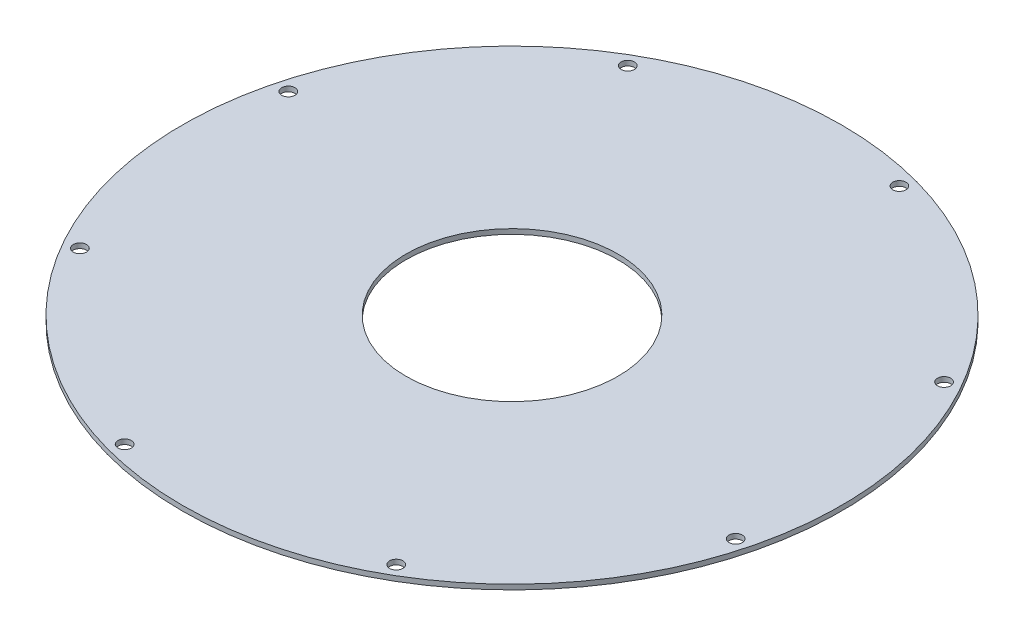
SolidWorks part; units mm, degrees
material "Thornel Mat VMA"
ref_plane "Front Plane" through (0, 0, 0) normal (0, 0, 1) x (1, 0, 0)
ref_plane "Top Plane" through (0, 0, 0) normal (0, 1, 0) x (1, 0, 0)
ref_plane "Right Plane" through (0, 0, 0) normal (1, 0, 0) x (0, 0, -1)
sketch "Sketch1" plane through (0, 0, 0) normal (0, 1, 0) x (1, 0, 0)
  circle A0 centre (0, 0) radius 32
  circle A1 centre (0, 0) radius 99.5
  dimension "D1" = 64
  dimension "D2" = 199
extrude "Base" add sketch "Sketch1" along normal mid plane 1.5
sketch "Sketch2" plane through (0, 0.75, 0) normal (0, 1, 0) x (1, 0, 0)
  line L0 (24.7172, 92.2459) -> (25.7525, 96.1096) construction
  line L1 (24.7172, 92.2459) -> (0, 0) construction
  line L2 (0, 0) -> (0, 99.5) construction
  circle A0 centre (24.7172, 92.2459) radius 2
  circle A2 centre (0, 0) radius 99.5 construction
  dimension "D1" = 4
  dimension "D2" = 4
  dimension "D3" = 15
extrude "Structural Hole" cut sketch "Sketch2" against normal through all
pattern_circular "Structural Hole Pattern" count 8 over 360 about axis through (0, 0, 0) along (0, 1, 0) of "Structural Hole"
equation "\"lift_fan_diameter\"=64"
equation "\"D1@Sketch1\"=\"lift_fan_diameter\""
equation "\"outer_diameter\"=199"
equation "\"D2@Sketch1\"=\"outer_diameter\""
equation "\"bolt_diameter\"=4"
equation "\"D1@Sketch2\"=\"bolt_diameter\""
equation "\"wall_thickness\"= 4"
equation "\"D2@Sketch2\"=\"wall_thickness\""
